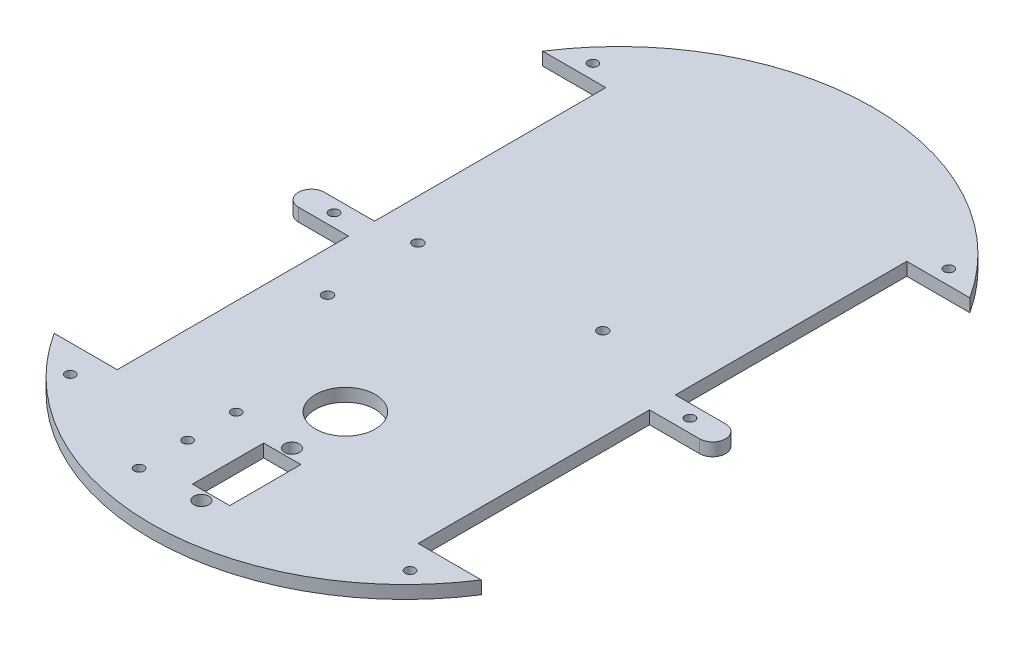
SolidWorks part; units mm, degrees
material "Acrylic (Medium-high impact)"
ref_plane "Front Plane" through (0, 0, 0) normal (0, 0, 1) x (1, 0, 0)
ref_plane "Top Plane" through (0, 0, 0) normal (0, 1, 0) x (1, 0, 0)
ref_plane "Right Plane" through (0, 0, 0) normal (1, 0, 0) x (0, 0, -1)
sketch "Sketch1" plane through (0, 0, 0) normal (0, 1, 0) x (1, 0, 0)
  line L0 (-62, 0) -> (62, 0) construction
  line L1 (-46.5, 0) -> (46.5, 0) construction
  line L2 (46.5, -4) -> (46.5, 4) construction
  line L3 (62, 4) -> (46.5, 4)
  line L4 (46.5, 4) -> (46.5, 75.5)
  line L5 (46.5, 75.5) -> (66, 75.5)
  line L6 (0, -125) -> (0, 125) construction
  line L7 (-46.5, -4) -> (-46.5, 4) construction
  line L8 (-46.5, 75.5) -> (-66, 75.5)
  line L9 (-46.5, 4) -> (-46.5, 75.5)
  line L10 (-62, 4) -> (-46.5, 4)
  line L11 (-62, -4) -> (-46.5, -4)
  line L12 (-46.5, -4) -> (-46.5, -75.5)
  line L13 (-46.5, -75.5) -> (-66, -75.5)
  line L14 (46.5, -75.5) -> (66, -75.5)
  line L15 (46.5, -4) -> (46.5, -75.5)
  line L16 (62, -4) -> (46.5, -4)
  arc A0 (62, 4) -> (62, -4) centre (62, 0) cw
  arc A1 (66, 75.5) -> (-66, 75.5) centre (0, 33) ccw
  arc A2 (-62, 4) -> (-62, -4) centre (-62, 0) ccw
  arc A3 (66, -75.5) -> (-66, -75.5) centre (0, -33) cw
  point P4 (0, 0)
  point P13 (66, 0)
  point P14 (0, 111.5)
  point P23 (0, 0)
  dimension "D4" = 71.5
  dimension "D3" = 4
  dimension "D1" = 66
  dimension "D2" = 46.5
  dimension "D5" = 36
  dimension "D6" = 66
extrude "Plate" add sketch "Sketch1" along normal blind 4
sketch "Sketch2" plane through (0, 4, 0) normal (0, 1, 0) x (1, 0, 0)
  line L0 (0, 0) -> (55, 0) construction
  line L1 (0, 0) -> (0, 80) construction
  line L2 (0, 80) -> (55, 80) construction
  line L3 (46.5, 75.5) -> (66, 75.5) construction
  line L4 (46.5, 4) -> (46.5, 75.5) construction
  line L5 (66, -75.5) -> (46.5, -75.5) construction
  line L7 (46.5, -75.5) -> (46.5, -4) construction
  circle A0 centre (55, 0) radius 1.5
  circle A1 centre (55, 80) radius 1.5
  circle A2 centre (-55, 0) radius 1.5
  circle A3 centre (-55, 80) radius 1.5
  circle A4 centre (52.5, -84) radius 1.5
  circle A5 centre (-52.5, -84) radius 1.5
  dimension "D3" = 1.5
  dimension "D5" = 3
  dimension "D1" = 8.5
  dimension "D2" = 4.5
  dimension "D4" = 8.5
  dimension "D6" = 8.5
  dimension "D7" = 6
extrude "Plate mountings" cut sketch "Sketch2" against normal through all
sketch "Sketch3" plane through (0, 4, 0) normal (0, 1, 0) x (1, 0, 0)
  line L0 (-16.75, -98.5) -> (-16.75, -109.6922) construction
  line L1 (66, -75.5) -> (46.5, -75.5) construction
  line L2 (7.25, -72.5) -> (-4.25, -72.5)
  line L3 (7.25, -72.5) -> (7.25, -94.5)
  line L4 (7.25, -94.5) -> (-4.25, -94.5)
  line L5 (-4.25, -72.5) -> (-4.25, -94.5)
  line L6 (46.5, -75.5) -> (46.5, -4) construction
  line L7 (-4.25, -83.5) -> (7.25, -83.5) construction
  line L8 (0, 0) -> (0, -51.5) construction
  circle A0 centre (-16.75, -98.5) radius 1.5
  circle A1 centre (1.5, -69.5) radius 2.31
  circle A2 centre (1.5, -97.5) radius 2.31
  circle A3 centre (-16.75, -83.5) radius 1.5
  circle A4 centre (-16.75, -68.5) radius 1.5
  arc A5 (-66, -75.5) -> (66, -75.5) centre (0, -33) ccw construction
  circle A6 centre (0, -51.5) radius 9.25
  point P11 (1.5, -72.5)
  dimension "D1" = 12.5
  dimension "D4" = 3
  dimension "D5" = 4.62
  dimension "D6" = 3
  dimension "D13" = 18.5
  dimension "D2" = 22
  dimension "D3" = 11.5
  dimension "D7" = 15
  dimension "D9" = 3
  dimension "D10" = 45
  dimension "D11" = 11.1922
  dimension "D12" = 17
  dimension "D8" = 3
extrude "Cut-Extrude1" cut sketch "Sketch3" against normal through all
sketch "Sketch4" plane through (0, 4, 0) normal (0, 1, 0) x (1, 0, 0)
  line L2 (32.08, 12.5) -> (-36.5, 12.5) construction
  line L4 (-46.5, 75.5) -> (-46.5, 4) construction
  circle A0 centre (18.11, 9.96) radius 1.59
  circle A1 centre (-33.96, 4.88) radius 1.59
  circle A2 centre (-33.96, -23.06) radius 1.59
  point P5 (32.08, 0)
  dimension "D4" = 3.18
  dimension "D7" = 7.62
  dimension "D9" = 35.56
  dimension "D10" = 12.5
  dimension "D11" = 2.54
  dimension "D5" = 3.18
  dimension "D6" = 3.18
  dimension "D2" = 68.58
  dimension "D3" = 13.97
  dimension "D8" = 66.04
  dimension "D12" = 10
extrude "Cut-Extrude2" cut sketch "Sketch4" against normal through all
